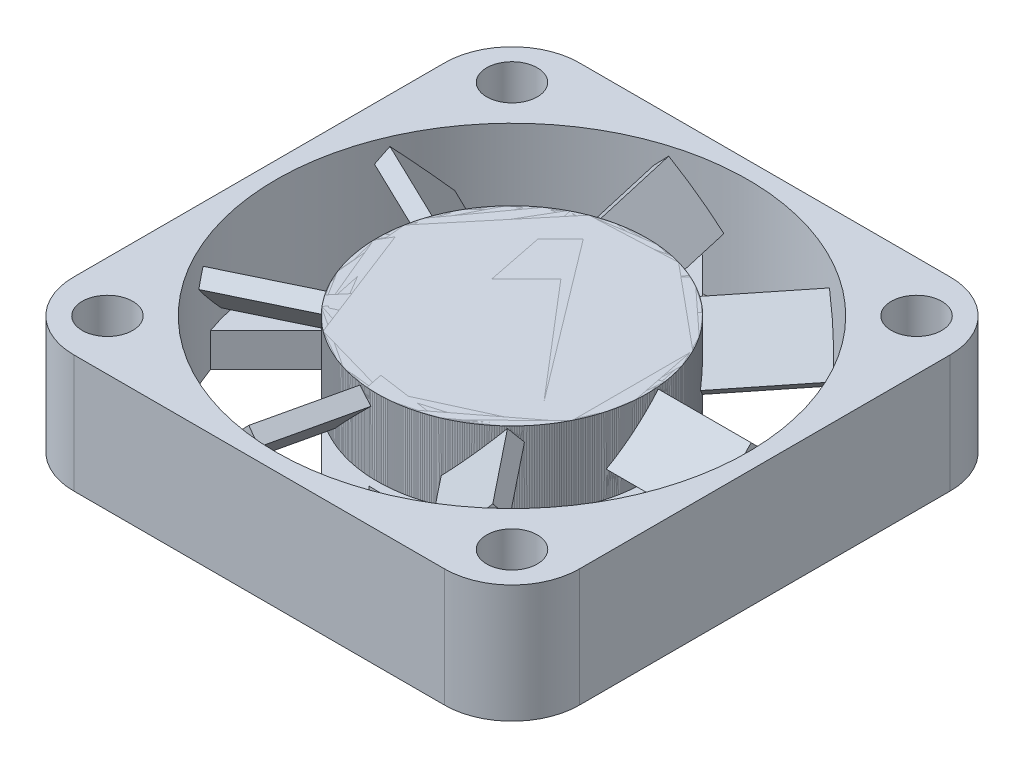
SolidWorks part; units mm, degrees
ref_plane "Front Plane" through (0, 0, 0) normal (0, 0, 1) x (1, 0, 0)
ref_plane "Top Plane" through (0, 0, 0) normal (0, 1, 0) x (1, 0, 0)
ref_plane "Right Plane" through (0, 0, 0) normal (1, 0, 0) x (0, 0, -1)
sketch "Sketch1" plane through (0, 0, 0) normal (0, 1, 0) x (1, 0, 0)
  line L0 (-15, 15) -> (15, -15) construction
  line L1 (-11, 15) -> (11, 15)
  line L2 (-15, 11) -> (-15, -11)
  line L3 (-11, -15) -> (11, -15)
  line L4 (15, 11) -> (15, -11)
  line L5 (12, 12) -> (-12, 12) construction
  line L6 (-12, 12) -> (-12, -12) construction
  line L7 (-12, -12) -> (12, -12) construction
  line L8 (12, -12) -> (12, 12) construction
  line L9 (-12, -12) -> (12, 12) construction
  circle A0 centre (0, 0) radius 14
  circle A1 centre (-12, 12) radius 1.5
  circle A2 centre (12, 12) radius 1.5
  circle A3 centre (12, -12) radius 1.5
  circle A4 centre (-12, -12) radius 1.5
  arc A5 (11, 15) -> (15, 11) centre (11, 11) cw
  arc A6 (11, -15) -> (15, -11) centre (11, -11) ccw
  arc A7 (-15, -11) -> (-11, -15) centre (-11, -11) ccw
  arc A8 (-11, 15) -> (-15, 11) centre (-11, 11) ccw
  point P17 (15, 15)
  dimension "D2" = 28
  dimension "D3" = 3
  dimension "D5" = 4
  dimension "D1" = 30
  dimension "D4" = 24
extrude "Boss-Extrude1" add sketch "Sketch1" along normal blind 7
sketch "Sketch2" plane through (0, 0, 0) normal (0, -1, 0) x (1, 0, 0)
  line L0 (-5.6569, 5.6569) -> (2.4672, 13.7809)
  line L1 (4.7016, 13.1869) -> (-0.501, 7.9843)
  line L2 (0, 0) -> (0, 3.9858) construction
  line L3 (5.6569, 5.6569) -> (13.7809, -2.4672)
  line L4 (13.1869, -4.7016) -> (7.9843, 0.501)
  line L5 (5.6569, -5.6569) -> (-2.4672, -13.7809)
  line L6 (-4.7016, -13.1869) -> (0.501, -7.9843)
  line L7 (-5.6569, -5.6569) -> (-13.7809, 2.4672)
  line L8 (-13.1869, 4.7016) -> (-7.9843, -0.501)
  arc A0 (-5.6569, 5.6569) -> (-7.9843, -0.501) centre (0, 0) ccw
  circle A1 centre (0, 0) radius 14 construction
  arc A2 (4.7016, 13.1869) -> (2.4672, 13.7809) centre (0, 0) ccw
  arc A3 (13.1869, -4.7016) -> (13.7809, -2.4672) centre (0, 0) ccw
  arc A4 (-4.7016, -13.1869) -> (-2.4672, -13.7809) centre (0, 0) ccw
  arc A5 (-13.1869, 4.7016) -> (-13.7809, 2.4672) centre (0, 0) ccw
  arc A6 (5.6569, 5.6569) -> (-0.501, 7.9843) centre (0, 0) ccw
  arc A7 (5.6569, -5.6569) -> (7.9843, 0.501) centre (0, 0) ccw
  arc A8 (-5.6569, -5.6569) -> (0.501, -7.9843) centre (0, 0) ccw
  point P24 (0, 0)
  dimension "D2" = 16
  dimension "D1" = 135
  dimension "D3" = 2
  dimension "D4" = 4
extrude "Boss-Extrude2" add sketch "Sketch2" against normal blind 2
sketch "Sketch3" plane through (0, 7, 0) normal (0, 1, 0) x (1, 0, 0)
  circle A0 centre (0, 0) radius 8
  dimension "D1" = 16
extrude "Boss-Extrude3" add sketch "Sketch3" against normal offset from surface (4.5 mm away) 0.5 separate body up to face at (0, 2, 0)
sketch "Sketch4" plane through (0, 0, 0) normal (1, 0, 0) x (0, 0, -1)
  line L0 (-2.1213, 4.0429) -> (0.7071, 6.8713)
  line L1 (-2.1213, 4.0429) -> (-1.4142, 3.3358)
  line L2 (0.7071, 6.8713) -> (1.4142, 6.1642)
  line L3 (-1.4142, 3.3358) -> (1.4142, 6.1642)
  line L4 (0, 0) -> (0, 4.75) construction
  line L5 (-11, 0) -> (11, 0) construction
  line L6 (0, 4.75) -> (8, 4.75) construction
  line L7 (8, 2.5) -> (8, 7) construction
  dimension "D1" = 45
  dimension "D2" = 1
  dimension "D3" = 4
extrude "Boss-Extrude4" add sketch "Sketch4" along normal offset from surface (13.4815 mm away) 0.5
pattern_circular "CirPattern3" count 7 over 360 about axis through (0, 0, 0) along (0, 1, 0) of bodies 104
